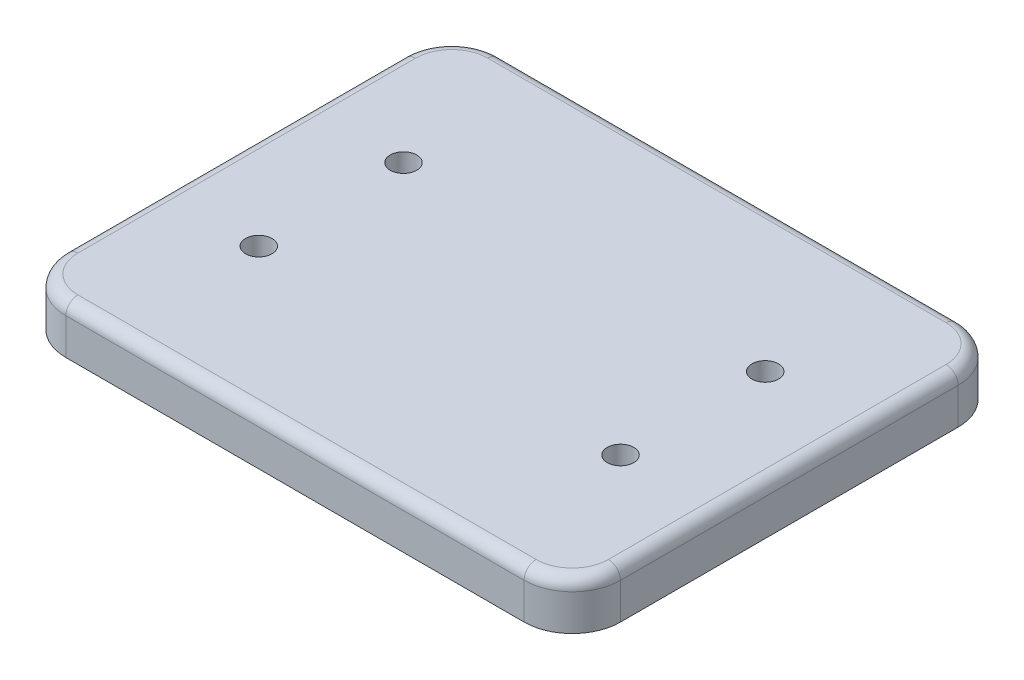
SolidWorks part; units mm, degrees
ref_plane "Front Plane" through (0, 0, 0) normal (0, 0, 1) x (1, 0, 0)
ref_plane "Top Plane" through (0, 0, 0) normal (0, 1, 0) x (1, 0, 0)
ref_plane "Right Plane" through (0, 0, 0) normal (1, 0, 0) x (0, 0, -1)
sketch "Sketch1" plane through (0, 0, 0) normal (0, 1, 0) x (1, 0, 0)
  line L1 (95, 90) -> (-95, 90)
  line L2 (115, 70) -> (115, -70)
  line L3 (95, -90) -> (-95, -90)
  line L4 (-115, 70) -> (-115, -70)
  line L5 (115, 90) -> (-115, -90) construction
  line L6 (115, -90) -> (-115, 90) construction
  arc A0 (-95, 90) -> (-115, 70) centre (-95, 70) ccw
  arc A1 (115, -70) -> (95, -90) centre (95, -70) cw
  arc A2 (95, 90) -> (115, 70) centre (95, 70) cw
  arc A3 (-95, -90) -> (-115, -70) centre (-95, -70) cw
  point P0 (0, 0)
  dimension "D3" = 20
  dimension "D1" = 230
  dimension "D2" = 180
extrude "Boss-Extrude1" add sketch "Sketch1" along normal blind 20
fillet "Fillet1" radius 5 8 edges at (0, 20, -90) (109.1421, 20, -84.1421) (115, 20, 0) (109.1421, 20, 84.1421) (0, 20, 90) (-109.1421, 20, 84.1421) (-115, 20, 0) (-109.1421, 20, -84.1421)
sketch "Sketch2" plane through (0, 20, 0) normal (0, 1, 0) x (1, 0, 0)
  circle A0 centre (-75, 30) radius 5.5
  circle A1 centre (75, 30) radius 5.5
  point P4 (0, 0)
  dimension "D4" = 11
  dimension "D1" = 30
  dimension "D2" = 75
  dimension "D3" = 75
extrude "Cut-Extrude1" cut sketch "Sketch2" against normal through all
sketch "Sketch3" plane through (0, 0, 0) normal (0, -1, 0) x (1, 0, 0)
  circle A0 centre (-75, -30) radius 9
  circle A1 centre (75, -30) radius 9
  dimension "D1" = 18
extrude "Cut-Extrude4" cut sketch "Sketch3" against normal blind 11
mirror "Mirror1" about plane through (0, 0, 0) normal (0, 0, 1) of "Cut-Extrude4", "Cut-Extrude1"
